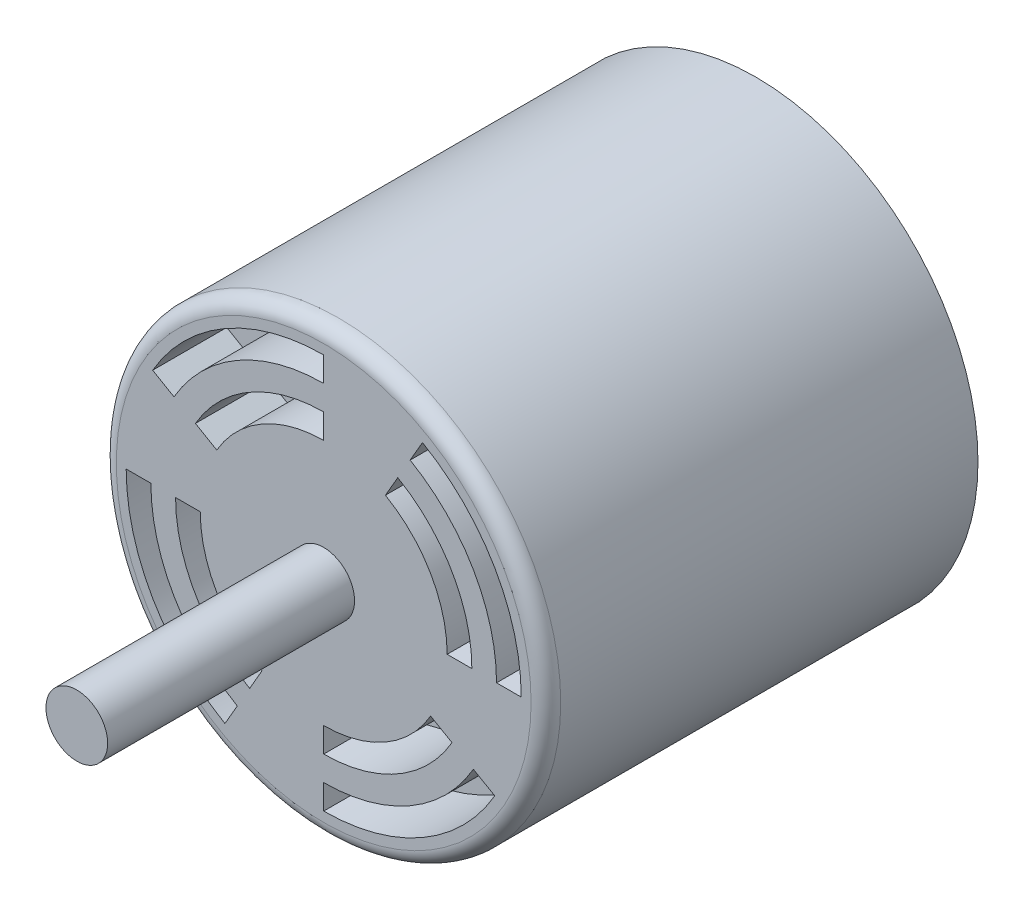
SolidWorks part; units mm, degrees
ref_plane "Front Plane" through (0, 0, 0) normal (0, 0, 1) x (1, 0, 0)
ref_plane "Top Plane" through (0, 0, 0) normal (0, 1, 0) x (1, 0, 0)
ref_plane "Right Plane" through (0, 0, 0) normal (1, 0, 0) x (0, 0, -1)
sketch "Sketch1" plane through (0, 0, 0) normal (0, 0, 1) x (1, 0, 0)
  circle A0 centre (0, 0) radius 22.86
  dimension "D1" = 45.72
extrude "Boss-Extrude1" add sketch "Sketch1" along normal blind 44.45 contours A0
sketch "Sketch2" plane through (0, 0, 44.45) normal (0, 0, 1) x (1, 0, 0)
  circle A0 centre (0, 0) radius 3.175
  dimension "D1" = 6.35
extrude "Boss-Extrude2" add sketch "Sketch2" along normal blind 25.4
sketch "Sketch3" plane through (0, 0, 44.45) normal (0, 0, 1) x (1, 0, 0)
  line L0 (12.7, 0) -> (15.24, 0)
  line L1 (6.35, 10.9985) -> (7.62, 13.1982)
  line L2 (8.89, 15.3979) -> (10.16, 17.5976)
  line L3 (17.78, 0) -> (20.32, 0)
  line L4 (15.3979, -8.89) -> (17.5976, -10.16)
  line L5 (10.9985, -6.35) -> (13.1982, -7.62)
  line L6 (0, -12.7) -> (0, -15.24)
  line L7 (0, -17.78) -> (0, -20.32)
  line L8 (-8.89, -15.3979) -> (-10.16, -17.5976)
  line L9 (-6.35, -10.9985) -> (-7.62, -13.1982)
  line L10 (-12.7, 0) -> (-15.24, 0)
  line L11 (-17.78, 0) -> (-20.32, 0)
  line L12 (-15.3979, 8.89) -> (-17.5976, 10.16)
  line L13 (-10.9985, 6.35) -> (-13.1982, 7.62)
  line L14 (0, 12.7) -> (0, 15.24)
  line L15 (0, 17.78) -> (0, 20.32)
  arc A0 (12.7, 0) -> (6.35, 10.9985) centre (0, 0) ccw
  arc A1 (15.24, 0) -> (7.62, 13.1982) centre (0, 0) ccw
  arc A2 (20.32, 0) -> (10.16, 17.5976) centre (0, 0) ccw
  arc A3 (17.78, 0) -> (8.89, 15.3979) centre (0, 0) ccw
  circle A4 centre (0, 0) radius 20.32 construction
  circle A5 centre (0, 0) radius 17.78 construction
  circle A6 centre (0, 0) radius 15.24 construction
  circle A7 centre (0, 0) radius 12.7 construction
  arc A8 (0, -12.7) -> (10.9985, -6.35) centre (0, 0) ccw
  arc A9 (0, -15.24) -> (13.1982, -7.62) centre (0, 0) ccw
  arc A10 (0, -17.78) -> (15.3979, -8.89) centre (0, 0) ccw
  arc A11 (0, -20.32) -> (17.5976, -10.16) centre (0, 0) ccw
  arc A12 (-12.7, 0) -> (-6.35, -10.9985) centre (0, 0) ccw
  arc A13 (-15.24, 0) -> (-7.62, -13.1982) centre (0, 0) ccw
  arc A14 (-17.78, 0) -> (-8.89, -15.3979) centre (0, 0) ccw
  arc A15 (-20.32, 0) -> (-10.16, -17.5976) centre (0, 0) ccw
  arc A16 (0, 12.7) -> (-10.9985, 6.35) centre (0, 0) ccw
  arc A17 (0, 15.24) -> (-13.1982, 7.62) centre (0, 0) ccw
  arc A18 (0, 17.78) -> (-15.3979, 8.89) centre (0, 0) ccw
  arc A19 (0, 20.32) -> (-17.5976, 10.16) centre (0, 0) ccw
  point P44 (0, 0)
  dimension "D1" = 25.4
  dimension "D5" = 60
  dimension "D2" = 2.54
  dimension "D3" = 7.62
  dimension "D4" = 5.08
  dimension "D6" = 4
extrude "Cut-Extrude1" cut sketch "Sketch3" against normal blind 7.62
fillet "Fillet1" radius 1.524 1 edges at (22.86, 0, 44.45)
